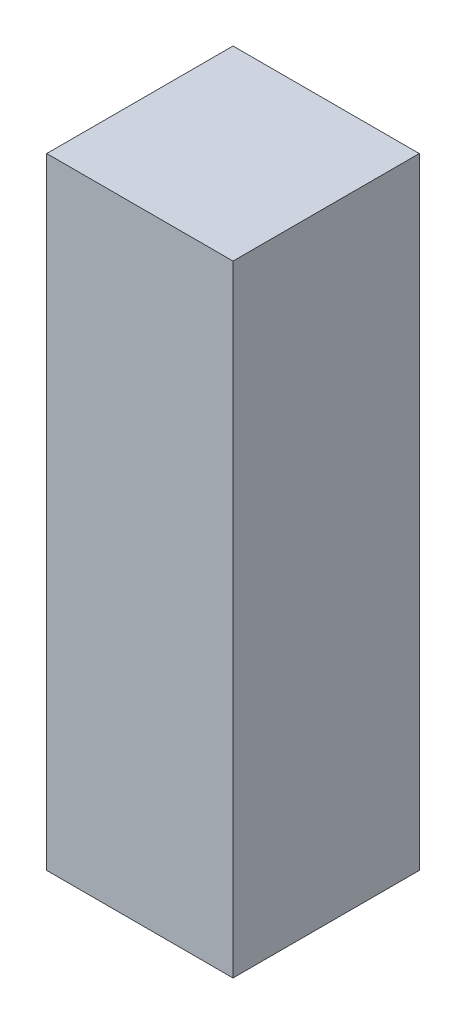
SolidWorks part; units mm, degrees
ref_plane "Front Plane" through (0, 0, 0) normal (0, 0, 1) x (1, 0, 0)
ref_plane "Top Plane" through (0, 0, 0) normal (0, 1, 0) x (1, 0, 0)
ref_plane "Right Plane" through (0, 0, 0) normal (1, 0, 0) x (0, 0, -1)
other "Configuration Table"
sketch "Sketch1" plane through (0, 0, 0) normal (0, 0, 1) x (1, 0, 0)
  line L1 (-6, 20) -> (6, 20)
  line L2 (-6, 20) -> (-6, 60)
  line L3 (-6, 60) -> (6, 60)
  line L4 (6, 20) -> (6, 60)
extrude "UCY_kilit_pimi_12x40_1" add sketch "Sketch1" against normal blind 12 from offset 168 separate body
